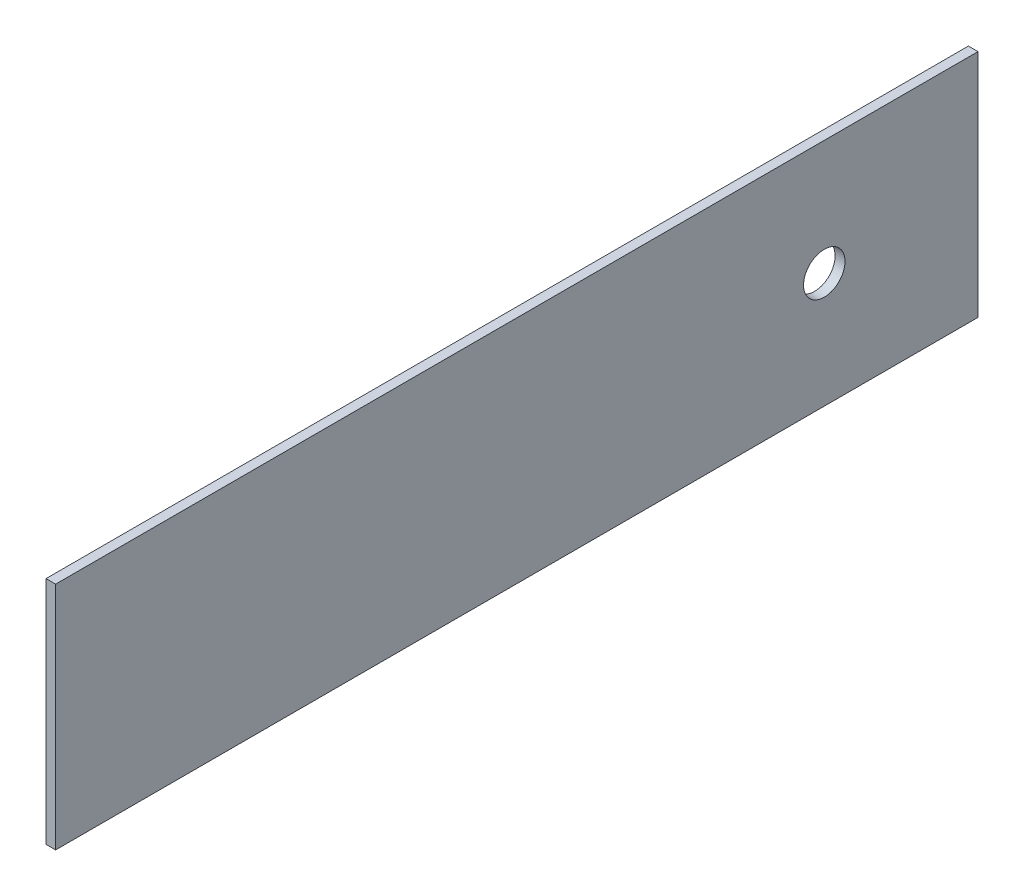
SolidWorks part; units mm, degrees
ref_plane "Front Plane" through (0, 0, 0) normal (0, 0, 1) x (1, 0, 0)
ref_plane "Top Plane" through (0, 0, 0) normal (0, 1, 0) x (1, 0, 0)
ref_plane "Right Plane" through (0, 0, 0) normal (1, 0, 0) x (0, 0, -1)
sketch "Sketch1" plane through (0, 0, 0) normal (1, 0, 0) x (0, 0, -1)
  line L1 (0, 0) -> (304.8, 0)
  line L2 (0, 0) -> (0, -76.073)
  line L3 (0, -76.073) -> (304.8, -76.073)
  line L4 (304.8, 0) -> (304.8, -76.073)
  dimension "D1" = 76.073
  dimension "D2" = 304.8
extrude "Boss-Extrude1" add sketch "Sketch1" along normal blind 3.175
sketch "Sketch2" plane through (0, 0, 0) normal (0, 0, 1) x (1, 0, 0)
  line L0 (1.5875, 0) -> (1.5875, -76.073) construction
  line L1 (3.175, 0) -> (0, 0) construction
  line L2 (3.175, -76.073) -> (0, -76.073) construction
sketch "Sketch3" plane through (0, 0, -304.8) normal (0, 0, -1) x (-1, 0, 0)
  line L0 (-1.5875, 0) -> (-1.5875, -76.073) construction
  line L1 (-3.175, 0) -> (0, 0) construction
  line L2 (-3.175, -76.073) -> (0, -76.073) construction
sketch "Sketch6" plane through (3.175, 0, 0) normal (1, 0, 0) x (0, 0, -1)
  line L0 (304.8, -38.0365) -> (254, -38.0365) construction
  line L1 (304.8, 0) -> (304.8, -76.073) construction
hole_wizard "1/4 NPT Tapped Hole2" positions "3DSketch2" profile "Sketch7" size "1/4" standard "ANSI Inch" end condition through all
sketch3d "3DSketch2"
  point P0 (3.175, -38.0365, -254)
sketch "Sketch7" plane through (3.175, -38.0365, -254) normal (0, 1, 0) x (0, 0, -1)
  line L0 (0, 0) -> (0, 3.175)
  line L1 (0, 3.175) -> (5.5626, 3.175)
  line L2 (-6.558, 9.906) -> (-6.8546, 0) construction
  line L3 (5.5626, 3.175) -> (5.5626, 9.906)
  line L4 (5.5626, 9.906) -> (6.558, 9.906)
  line L5 (6.558, 9.906) -> (6.8546, 0)
  line L7 (6.8546, 0) -> (0, 0)
  line L8 (0, -6.35) -> (0, 107.95) construction
  line L11 (-5.5626, 9.906) -> (-6.558, 9.906) construction
  dimension "Thru Tap Drill Dia." = 11.1252
  dimension "Thru Tap Drill Depth" = 3.175
  dimension "Thread Dia." = 13.7092
  dimension "Thread Angle" = 3.43
  dimension "Thread Depth" = 9.906
